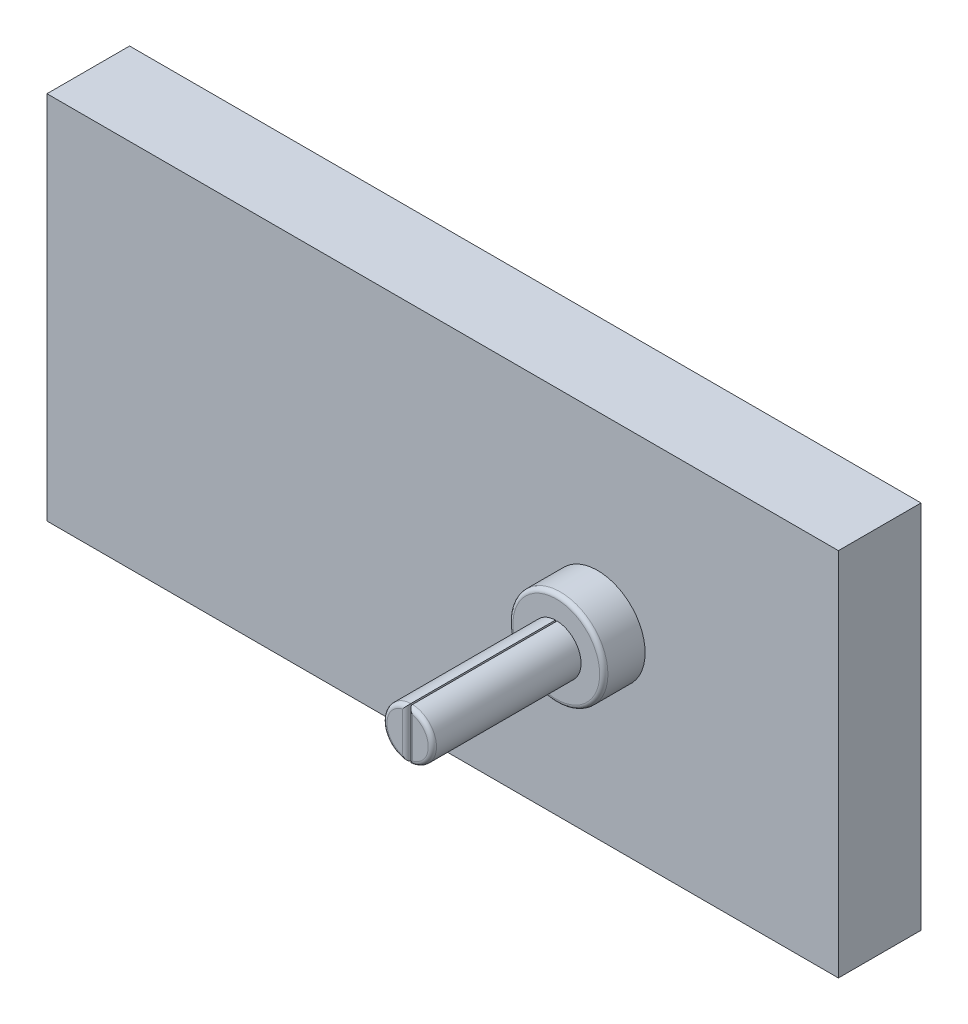
SolidWorks part; units mm, degrees
ref_plane "Front Plane" through (0, 0, 0) normal (0, 0, 1) x (1, 0, 0)
ref_plane "Top Plane" through (0, 0, 0) normal (0, 1, 0) x (1, 0, 0)
ref_plane "Right Plane" through (0, 0, 0) normal (1, 0, 0) x (0, 0, -1)
sketch "Sketch1" plane through (0, 0, 0) normal (0, 0, 1) x (1, 0, 0)
  line L1 (47.9, -22.4) -> (-47.9, -22.4)
  line L2 (47.9, -22.4) -> (47.9, 22.4)
  line L3 (47.9, 22.4) -> (-47.9, 22.4)
  line L4 (-47.9, -22.4) -> (-47.9, 22.4)
  line L5 (47.9, -22.4) -> (-47.9, 22.4) construction
  line L6 (47.9, 22.4) -> (-47.9, -22.4) construction
  point P0 (0, 0)
  dimension "D1" = 95.8
  dimension "D2" = 44.8
extrude "MainWall" add sketch "Sketch1" along normal blind 10
sketch "Sketch2" plane through (0, 0, 10) normal (0, 0, 1) x (1, 0, 0)
  line L0 (0, 22.4) -> (0, -22.4) construction
  line L1 (47.9, 22.4) -> (-47.9, 22.4) construction
  line L2 (-47.9, -22.4) -> (47.9, -22.4) construction
  line L3 (47.0086, 0) -> (-58.8214, 0) construction
  circle A0 centre (18.75, 0) radius 3
  dimension "D1" = 6
  dimension "D2" = 18.75
extrude "SpringAxle" add sketch "Sketch2" along normal blind 23
sketch "Sketch3" plane through (0, 0, 10) normal (0, 0, 1) x (1, 0, 0)
  circle A0 centre (18.75, 0) radius 5.75
  dimension "D1" = 11.5
extrude "SpoolSupportAxle" add sketch "Sketch3" along normal blind 5
sketch "Sketch4" plane through (0, 0, 33) normal (0, 0, 1) x (1, 0, 0)
  line L1 (18.85, -10) -> (18.65, -10)
  line L2 (18.85, -10) -> (18.85, 10)
  line L3 (18.85, 10) -> (18.65, 10)
  line L4 (18.65, -10) -> (18.65, 10)
  line L5 (18.85, -10) -> (18.65, 10) construction
  line L6 (18.85, 10) -> (18.65, -10) construction
  point P0 (18.75, 0)
  dimension "D1" = 20
  dimension "D2" = 0.2
extrude "Slice" cut sketch "Sketch4" against normal blind 18
fillet "Fillet1" radius 0.5 5 edges at (24.5, 0, 15) (21.75, 0, 33) (18.85, 0, 33) (15.75, 0, 33) (18.65, 0, 33)
